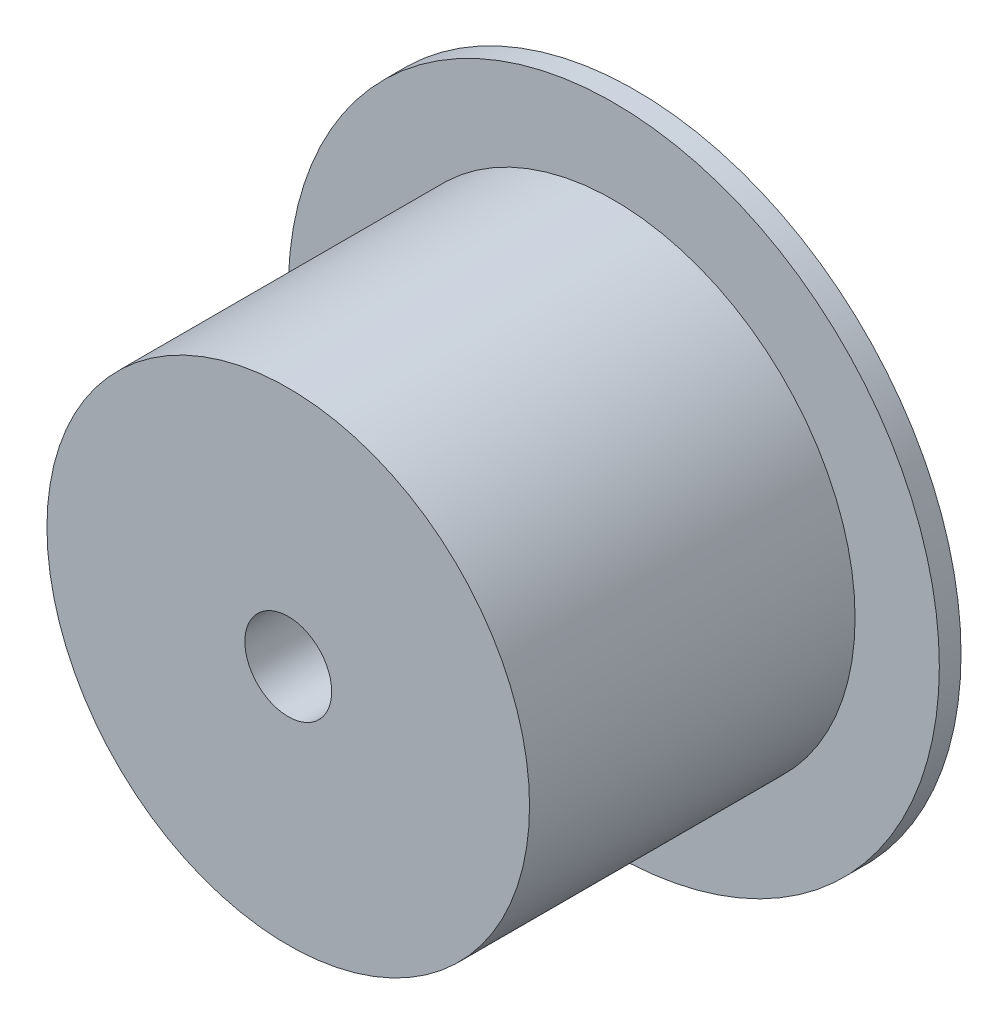
SolidWorks part; units mm, degrees
ref_plane "Ön Düzlem" through (0, 0, 0) normal (0, 0, 1) x (1, 0, 0)
ref_plane "Üst Düzlem" through (0, 0, 0) normal (0, 1, 0) x (1, 0, 0)
ref_plane "Sağ Düzlem" through (0, 0, 0) normal (1, 0, 0) x (0, 0, -1)
sketch "Çizim1" plane through (0, 0, 0) normal (0, 0, 1) x (1, 0, 0)
  circle A0 centre (-15.7997, 0) radius 15
  dimension "D1" = 30
extrude "Yükseklik-Ekstrüzyon1" add sketch "Çizim1" along normal blind 1
sketch "Çizim2" plane through (0, 0, 1) normal (0, 0, 1) x (1, 0, 0)
  circle A0 centre (-15.7997, 0) radius 11.118
extrude "Yükseklik-Ekstrüzyon2" add sketch "Çizim2" along normal blind 15
sketch "Çizim3" plane through (0, 0, 16) normal (0, 0, 1) x (1, 0, 0)
  circle A0 centre (-15.7997, 0) radius 2
  dimension "D1" = 4
extrude "Kes-Ekstrüzyon1" cut sketch "Çizim3" against normal through all
